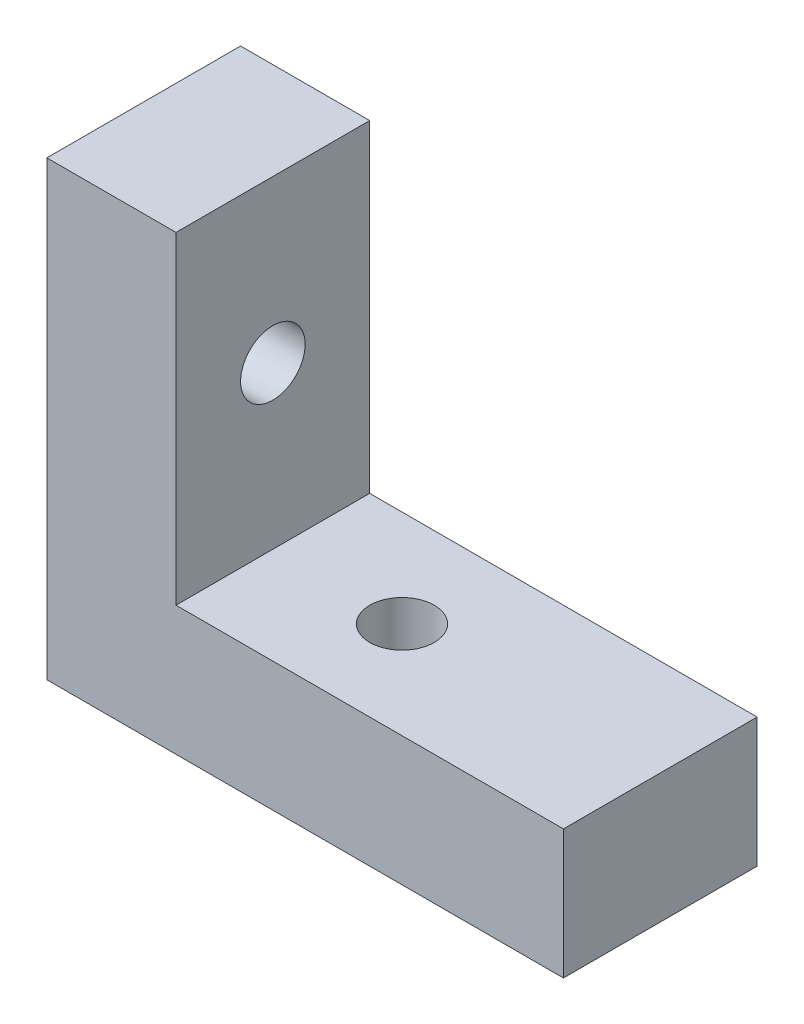
SolidWorks part; units mm, degrees
ref_plane "Front Plane" through (0, 0, 0) normal (0, 0, 1) x (1, 0, 0)
ref_plane "Top Plane" through (0, 0, 0) normal (0, 1, 0) x (1, 0, 0)
ref_plane "Right Plane" through (0, 0, 0) normal (1, 0, 0) x (0, 0, -1)
sketch "Sketch1" plane through (0, 0, 0) normal (0, 1, 0) x (1, 0, 0)
  line L1 (-40, -15) -> (40, -15)
  line L2 (-40, -15) -> (-40, 15)
  line L3 (-40, 15) -> (40, 15)
  line L4 (40, -15) -> (40, 15)
  point P0 (0, 0)
  dimension "D1" = 40
  dimension "D2" = 40
  dimension "D3" = 15
  dimension "D4" = 15
extrude "Boss-Extrude1" add sketch "Sketch1" along normal blind 20
sketch "Sketch2" plane through (0, 20, 0) normal (0, 1, 0) x (1, 0, 0)
  line L0 (-40, 15) -> (-40, -15)
  line L1 (-40, -15) -> (-20, -15)
  line L3 (-20, -15) -> (-20, 15)
  line L5 (-20, 15) -> (-40, 15)
  line L6 (40, -15) -> (40, 15) construction
  line L7 (40, 15) -> (-40, 15) construction
  dimension "D1" = 60
  dimension "D2" = 80
  dimension "D3" = 30
extrude "Boss-Extrude2" add sketch "Sketch2" along normal blind 50
sketch "Sketch3" plane through (0, 20, 0) normal (0, 1, 0) x (1, 0, 0)
  line L0 (40, 15) -> (-20, 15) construction
  line L1 (40, -15) -> (40, 15) construction
  circle A0 centre (0, 0) radius 5
  dimension "D1" = 10
  dimension "D2" = 15
  dimension "D3" = 40
extrude "Cut-Extrude1" cut sketch "Sketch3" against normal blind 50
sketch "Sketch4" plane through (-20, 0, 0) normal (1, 0, 0) x (0, 0, -1)
  line L0 (-15, 70) -> (15, 70) construction
  line L1 (-15, 70) -> (-15, 20) construction
  circle A0 centre (0, 45) radius 5
  dimension "D1" = 10
  dimension "D2" = 25
  dimension "D3" = 15
extrude "Cut-Extrude2" cut sketch "Sketch4" against normal blind 50
